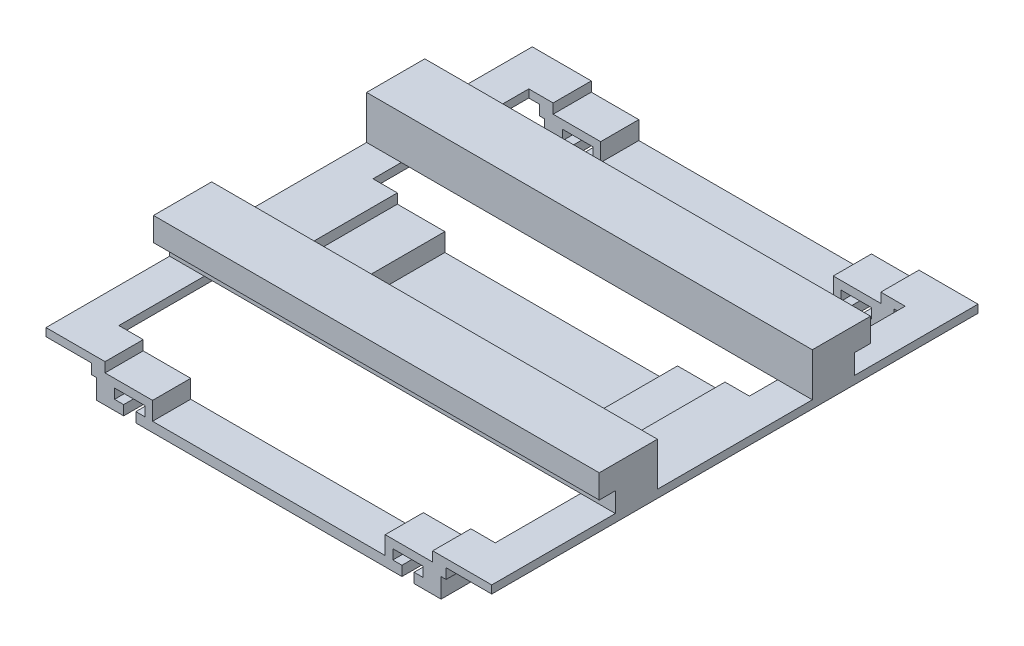
SolidWorks part; units mm, degrees
ref_plane "Front Plane" through (0, 0, 0) normal (0, 0, 1) x (1, 0, 0)
ref_plane "Top Plane" through (0, 0, 0) normal (0, 1, 0) x (1, 0, 0)
ref_plane "Right Plane" through (0, 0, 0) normal (1, 0, 0) x (0, 0, -1)
sketch "Sketch1" plane through (0, 0, 0) normal (0, 0, 1) x (-1, 0, 0)
  line L0 (-604.442, -1264.1289) -> (-490.142, -1264.1289)
  line L1 (-490.142, -1264.1289) -> (-490.142, -1238.7289)
  line L2 (-490.142, -1238.7289) -> (-477.442, -1238.7289)
  line L3 (-477.442, -1238.7289) -> (-477.442, -1189.5119)
  line L4 (-477.442, -1189.5119) -> (-409.7408, -1189.5119)
  line L5 (-409.7408, -1189.5119) -> (-409.7408, -1214.1204)
  line L6 (-409.7408, -1214.1204) -> (-432.6008, -1214.1204)
  line L7 (-432.6008, -1214.1204) -> (-432.6008, -1238.7289)
  line L8 (-432.6008, -1238.7289) -> (-356.4008, -1238.7289)
  line L9 (-356.4008, -1238.7289) -> (-356.4008, -1214.1204)
  line L10 (-356.4008, -1214.1204) -> (-379.2608, -1214.1204)
  line L11 (-379.2608, -1214.1204) -> (-379.2608, -1189.5119)
  line L12 (-379.2608, -1189.5119) -> (287.9768, -1189.5119)
  line L14 (-604.442, -1264.1289) -> (-604.442, -1284.0294)
  line L15 (-604.442, -1284.0294) -> (-456.4138, -1284.0294)
  line L16 (-337.2857, -1259.5419) -> (-337.2857, -1214.1204)
  line L17 (-337.2857, -1214.1204) -> (246.0017, -1214.1204)
  line L18 (-337.2857, -1259.5419) -> (-456.4138, -1259.5419)
  line L19 (-456.4138, -1259.5419) -> (-456.4138, -1284.0294)
  line L20 (365.1298, -1259.5419) -> (365.1298, -1284.0294)
  line L21 (246.0017, -1259.5419) -> (365.1298, -1259.5419)
  line L22 (246.0017, -1259.5419) -> (246.0017, -1214.1204)
  line L23 (513.158, -1284.0294) -> (365.1298, -1284.0294)
  line L24 (513.158, -1264.1289) -> (513.158, -1284.0294)
  line L25 (287.9768, -1214.1204) -> (287.9768, -1189.5119)
  line L26 (265.1168, -1214.1204) -> (287.9768, -1214.1204)
  line L27 (265.1168, -1238.7289) -> (265.1168, -1214.1204)
  line L28 (341.3168, -1238.7289) -> (265.1168, -1238.7289)
  line L29 (341.3168, -1214.1204) -> (341.3168, -1238.7289)
  line L30 (318.4568, -1214.1204) -> (341.3168, -1214.1204)
  line L31 (318.4568, -1189.5119) -> (318.4568, -1214.1204)
  line L32 (386.158, -1189.5119) -> (318.4568, -1189.5119)
  line L33 (386.158, -1238.7289) -> (386.158, -1189.5119)
  line L34 (398.858, -1238.7289) -> (386.158, -1238.7289)
  line L35 (398.858, -1264.1289) -> (398.858, -1238.7289)
  line L36 (513.158, -1264.1289) -> (398.858, -1264.1289)
  point P39 (-45.642, -1214.1204)
extrude "Extrude1" add sketch "Sketch1" along normal blind 1219.2
sketch "Sketch2" plane through (0, 1284.0294, 0) normal (0, 1, 0) x (1, 0, 0)
  line L0 (517.4827, -95.7141) -> (517.4827, -486.2674)
  line L3 (-426.1987, -732.9326) -> (517.4827, -732.9326)
  line L4 (-426.1987, -95.7141) -> (517.4827, -95.7141)
  line L5 (-426.1987, -95.7141) -> (-426.1987, -486.2674)
  line L6 (-426.1987, -486.2674) -> (517.4827, -486.2674)
  line L12 (-426.1987, -1123.4859) -> (-426.1987, -732.9326)
  line L13 (-426.1987, -1123.4859) -> (517.4827, -1123.4859)
  line L14 (517.4827, -1123.4859) -> (517.4827, -732.9326)
extrude "Extrude2" cut sketch "Sketch2" against normal through all
sketch "Sketch3" plane through (-513.158, 0, 0) normal (-1, 0, 0) x (0, 0, 1)
  line L0 (309.9748, 1284.0294) -> (309.9748, 1333.5171)
  line L1 (1219.2, 1284.0294) -> (0, 1284.0294) construction
  line L2 (309.9748, 1333.5171) -> (269.5434, 1333.5171)
  line L3 (269.5434, 1333.5171) -> (269.5434, 1392.7202)
  line L4 (269.5434, 1392.7202) -> (415.3851, 1392.7202)
  line L5 (415.3851, 1392.7202) -> (415.3851, 1284.0294)
  line L6 (415.3851, 1284.0294) -> (309.9748, 1284.0294)
  line L7 (803.8149, 1284.0294) -> (909.2252, 1284.0294)
  line L8 (803.8149, 1392.7202) -> (803.8149, 1284.0294)
  line L9 (949.6566, 1392.7202) -> (803.8149, 1392.7202)
  line L11 (949.6566, 1333.5171) -> (949.6566, 1392.7202)
  line L12 (909.2252, 1333.5171) -> (949.6566, 1333.5171)
  line L13 (909.2252, 1284.0294) -> (909.2252, 1333.5171)
extrude "Extrude3" add sketch "Sketch3" against normal up to surface (1117.6 mm away) up to face at (604.442, 1274.0791, 609.6)
